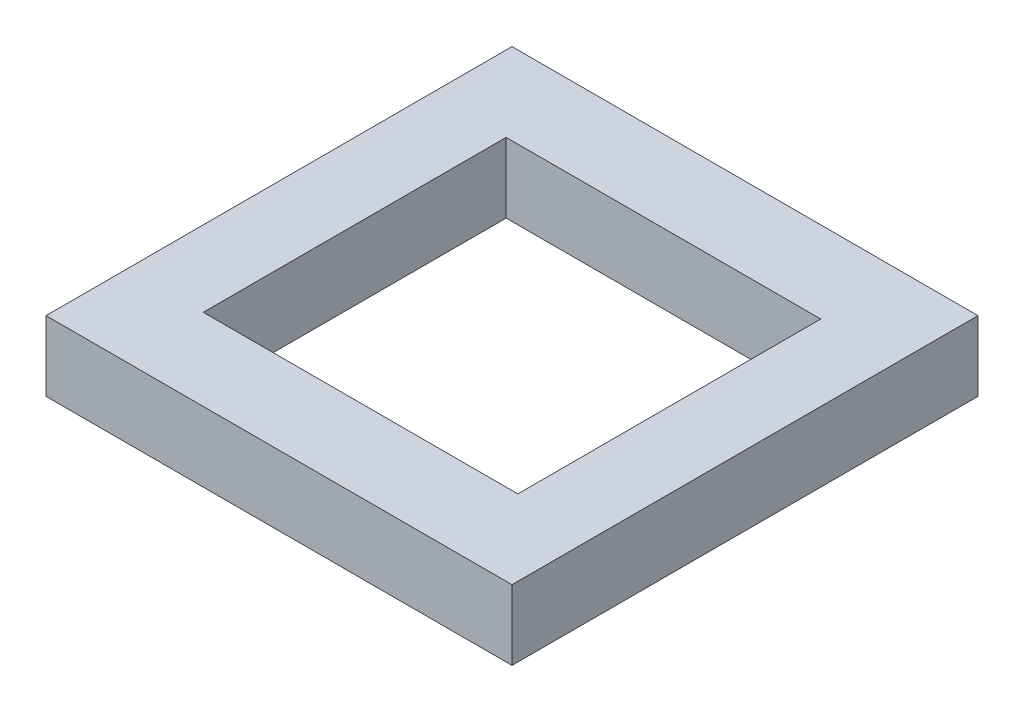
SolidWorks part; units mm, degrees
ref_plane "Front Plane" through (0, 0, 0) normal (0, 0, 1) x (1, 0, 0)
ref_plane "Top Plane" through (0, 0, 0) normal (0, 1, 0) x (1, 0, 0)
ref_plane "Right Plane" through (0, 0, 0) normal (1, 0, 0) x (0, 0, -1)
sketch "Sketch1" plane through (0, 0, 0) normal (0, 1, 0) x (1, 0, 0)
  line L1 (-20, 20) -> (20, 20)
  line L2 (-20, 20) -> (-20, -20)
  line L3 (-20, -20) -> (20, -20)
  line L4 (20, 20) -> (20, -20)
  line L5 (-20, 20) -> (20, -20) construction
  line L6 (-20, -20) -> (20, 20) construction
  line L7 (-13.5, 13) -> (13.5, 13)
  line L8 (-13.5, 13) -> (-13.5, -13)
  line L9 (-13.5, -13) -> (13.5, -13)
  line L10 (13.5, 13) -> (13.5, -13)
  line L11 (-13.5, 13) -> (13.5, -13) construction
  line L12 (-13.5, -13) -> (13.5, 13) construction
  point P0 (0, 0)
  point P6 (0, 0)
  dimension "D1" = 40
  dimension "D2" = 40
  dimension "D3" = 26
  dimension "D4" = 27
extrude "Boss-Extrude1" add sketch "Sketch1" along normal blind 6
